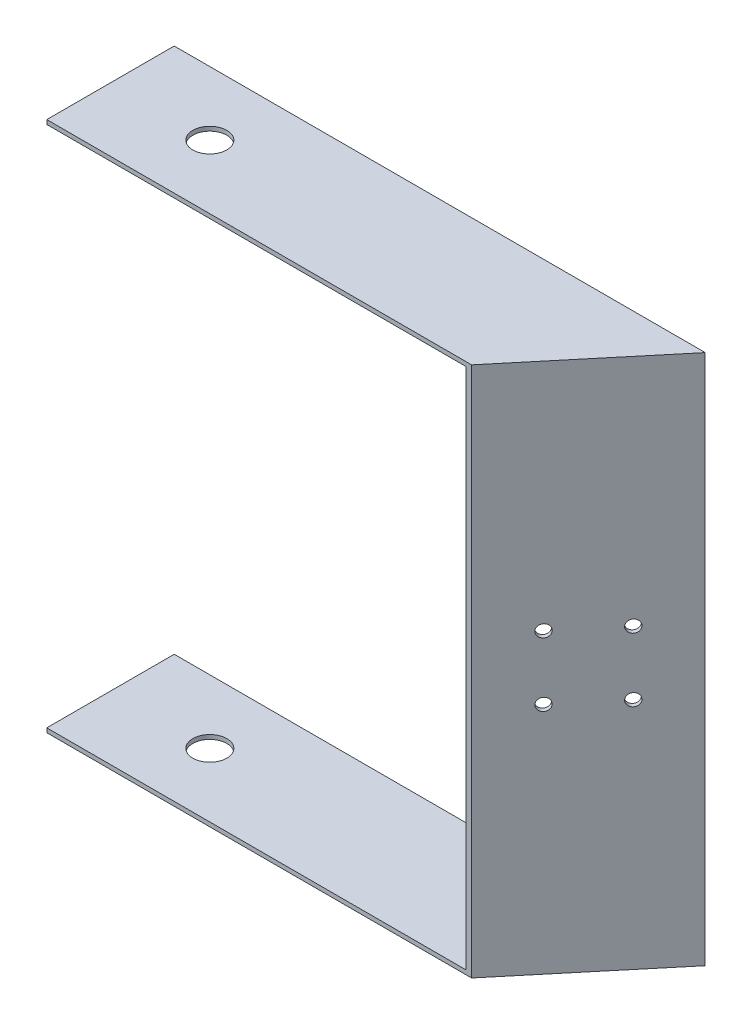
SolidWorks part; units mm, degrees
ref_plane "Front Plane" through (0, 0, 0) normal (0, 0, 1) x (1, 0, 0)
ref_plane "Top Plane" through (0, 0, 0) normal (0, 1, 0) x (1, 0, 0)
ref_plane "Right Plane" through (0, 0, 0) normal (1, 0, 0) x (0, 0, -1)
sketch "Sketch1" plane through (0, 0, 0) normal (0, 0, 1) x (1, 0, 0)
  line L1 (0, 0) -> (125, 0)
  line L2 (0, 0) -> (0, 125)
  line L3 (0, 125) -> (125, 125)
  line L4 (125, 0) -> (125, 125)
  dimension "D1" = 125
  dimension "D2" = 125
extrude "Boss-Extrude1" add sketch "Sketch1" along normal blind 30
sketch "Sketch2" plane through (0, 125, 0) normal (0, 1, 0) x (1, 0, 0)
  line L0 (125, 0) -> (100, -30)
  line L1 (125, -30) -> (0, -30) construction
  line L2 (0, -30) -> (0, 0) construction
  line L3 (125, 0) -> (125, -30)
  line L4 (125, -30) -> (100, -30)
  dimension "D1" = 100
extrude "Cut-Extrude1" cut sketch "Sketch2" against normal blind 125
shell "Shell1" thickness 1
sketch "Sketch3" plane through (0, 0, 0) normal (0, -1, 0) x (-1, 0, 0)
  circle A0 centre (-23.3802, -15) radius 4
  dimension "D1" = 8
extrude "Cut-Extrude2" cut sketch "Sketch3" against normal blind 125
sketch "Sketch4" plane through (73.7705, 0, 61.4754) normal (0.7682, 0, 0.6402) x (0.6402, 0, -0.7682)
  line L0 (60.4974, 125) -> (60.4974, 0) construction
  line L1 (80.023, 125) -> (40.9718, 125) construction
  line L2 (80.023, 0) -> (40.9718, 0) construction
  line L3 (40.9718, 62.5) -> (80.023, 62.5) construction
  line L4 (40.9718, 0) -> (40.9718, 125) construction
  line L5 (80.023, 0) -> (80.023, 125) construction
  line L7 (52.9974, 70) -> (67.9974, 70)
  line L8 (52.9974, 70) -> (52.9974, 55)
  line L9 (52.9974, 55) -> (67.9974, 55)
  line L10 (67.9974, 70) -> (67.9974, 55)
  circle A0 centre (52.9974, 70) radius 1.45
  circle A1 centre (67.9974, 70) radius 1.45
  circle A2 centre (52.9974, 55) radius 1.45
  circle A3 centre (67.9974, 55) radius 1.45
  point P20 (53.2907, 55.2933)
  dimension "D1" = 2.9
  dimension "D2" = 15
extrude "Cut-Extrude3" cut sketch "Sketch4" against normal blind 125 contours L7 A0 L8 | L8 A0 L7 | L7 A1 L10 | L10 A1 L7 | L8 A2 L9 | L9 A2 L8 | L9 A3 L10 | L10 A3 L9
